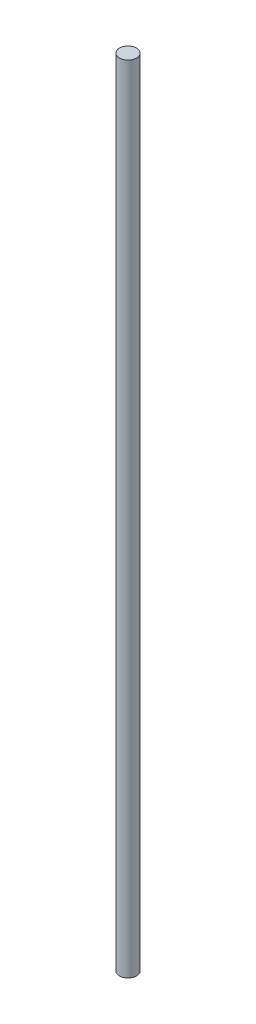
SolidWorks part; units mm, degrees
ref_plane "Front Plane" through (0, 0, 0) normal (0, 0, 1) x (1, 0, 0)
ref_plane "Top Plane" through (0, 0, 0) normal (0, 1, 0) x (1, 0, 0)
ref_plane "Right Plane" through (0, 0, 0) normal (1, 0, 0) x (0, 0, -1)
sketch "Sketch1" plane through (0, 0, 0) normal (0, 1, 0) x (1, 0, 0)
  circle A0 centre (0, 0) radius 4
extrude "Boss-Extrude1" add sketch "Sketch1" along normal blind 370
